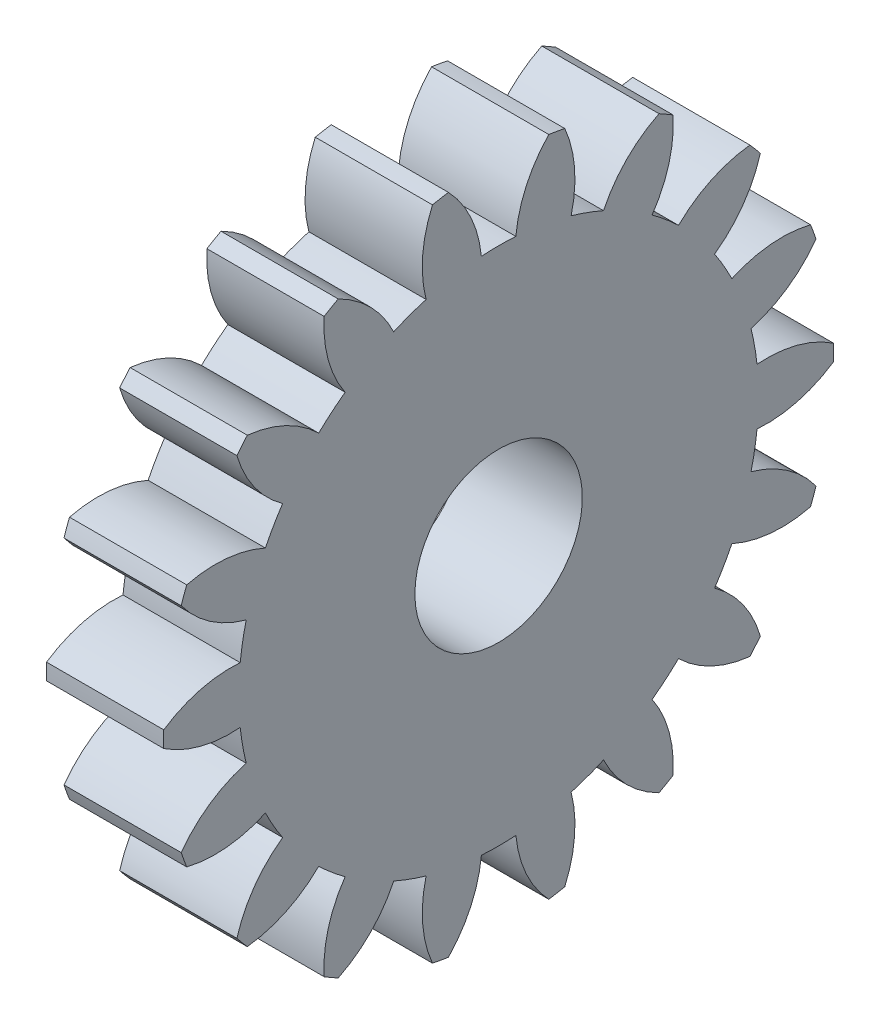
SolidWorks part; units mm, degrees
material "Cedar"
ref_plane "Plane1" through (0, 0, 0) normal (0, 0, 1) x (1, 0, 0)
ref_plane "Plane2" through (0, 0, 0) normal (0, 1, 0) x (1, 0, 0)
ref_plane "Plane3" through (0, 0, 0) normal (1, 0, 0) x (0, 0, -1)
sketch "HoldingSke" plane through (0, 0, 0) normal (0, 1, 0) x (1, 0, 0)
  line L0 (0, 0) -> (483.1367, -156.9806)
  line L1 (-15, 0) -> (100, 0) construction
  line L2 (0, 0) -> (-2.1039, 2.3779)
  line L3 (0, 0) -> (-11.863, 4.5341)
  line L4 (0, 0) -> (8.2133, 2.6687)
  line L5 (0, 0) -> (-47.5972, -17.7524)
  line L6 (0, 0) -> (-3.6847, -2.4861)
  line L7 (-2.1039, 2.3779) -> (8.8308, 51.9871)
  line L8 (-76.2, 54.61) -> (-69.596, 54.61)
  line L9 (-71.009, 38.7566) -> (-53.1078, 45.2721)
  line L10 (-76.2, 71.12) -> (104.1128, 71.12)
  line L11 (0, 0) -> (-4.445, 0)
  line L12 (-76.2, 101.6) -> (-76.1492, 101.6)
  line L13 (24.9733, 27.94) -> (52.9518, 28.4284)
  line L14 (24.9733, 27.94) -> (25.0241, 27.9398)
  line L15 (24.9733, 27.94) -> (100.4021, 29.52)
  circle A0 centre (0, 0) radius 3.175
  circle A1 centre (0, 0) radius 9.8552
  circle A2 centre (0, 0) radius 38.1
  circle A3 centre (0, 0) radius 3.175
  dimension "MHD" = 19.7104
  dimension "Hub_dia" = 76.2
  dimension "Bore" = 6.35
  dimension "MBD" = 6.35
  dimension "Num_teeth" = 18
  dimension "Pitch_radius" = 180.3128
  dimension "Pitch" = 508
  dimension "Width" = 4.445
  dimension "Overall_len" = 50.8
  dimension "Show_teeth" = 18
  dimension "Thickness" = 4.445
  dimension "OAL" = 50.8001
  dimension "T_dim" = 6.604
  dimension "Ap" = 20
  dimension "H" = 19.05
  dimension "Backlash" = 0.0508
  dimension "Addendum_fac" = 1
  dimension "Dedendum_fac" = 1.2
  dimension "Clearance_fac" = 0.2
  dimension "Dedendum_add" = 0.0508
sketch "BasProSke" plane through (0, 0, 0) normal (0, 1, 0) x (1, 0, 0)
  line L0 (-10, 0) -> (60, 0) construction
  line L1 (0, 0) -> (0, 12.7)
  line L2 (0, 0) -> (4.445, 0)
  line L3 (4.445, 0) -> (4.445, 12.7)
  line L4 (4.445, 12.7) -> (0, 12.7)
  dimension "Diameter" = 25.4
  dimension "Thickness" = 4.445
revolve "Base-Revolve" add sketch "BasProSke" angle 360 about L0
sketch "TooCutSke" plane through (0, 0, 0) normal (1, 0, 0) x (0, 0, -1)
  line L1 (0, 0) -> (0, 107) construction
  line L2 (0, 0) -> (-1.085, 11.3784) construction
  line L3 (0, 0) -> (-3.9571, 22.4417) construction
  line L4 (-1.085, 11.3784) -> (-1.9785, 11.2208) construction
  arc A0 (0.6537, 9.8335) -> (-0.6537, 9.8335) centre (0, 0) ccw
  arc A1 (1.9234, 12.5792) -> (-1.9234, 12.5792) centre (0, 0) ccw
  circle A2 centre (0, 0) radius 11.43 construction
  circle A3 centre (0, 0) radius 10.7407 construction
  arc A4 (-0.6537, 9.8335) -> (-1.9234, 12.5792) centre (-5.2046, 9.3954) ccw
  arc A5 (1.9234, 12.5792) -> (0.6537, 9.8335) centre (5.2046, 9.3954) ccw
  dimension "Root_dia" = 19.7104
  dimension "Overcut_dia" = 25.4508
  dimension "Pitch_dia" = 22.86
  dimension "Base_dia" = 21.4814
  dimension "Flank_rad" = 4.572
  dimension "Half_ang" = 10
  dimension "Half_CT" = 0.9073
extrude "ToothCut" cut sketch "TooCutSke" along normal through all
fillet "Breaks" [suppressed] radius 0.0254
fillet "RootFillets" [suppressed] radius 0.3048
pattern_circular "TeethCuts" count 18 every 20 about axis through (-10, 0, 0) along (1, 0, 0) of "ToothCut", "RootFillets", "Breaks"
sketch "HubNeaOneSke" plane through (0, 0, 0) normal (-1, 0, 0) x (0, 0, 1)
  circle A0 centre (0, 0) radius 9.8552
  dimension "Diameter" = 19.7104
extrude "HubNearOne" [suppressed] add sketch "HubNeaOneSke" along normal blind 46.3551
sketch "HubNeaBotSke" plane through (0, 0, 0) normal (-1, 0, 0) x (0, 0, 1)
  circle A0 centre (0, 0) radius 9.8552
  dimension "Diameter" = 19.7104
extrude "HubNearBoth" [suppressed] add sketch "HubNeaBotSke" along normal blind 23.1775
ref_plane "FarPln" through (4.445, 0, 0) normal (1, 0, 0) x (0, 0, -1)
sketch "HubFarSke" plane through (4.445, 0, 0) normal (1, 0, 0) x (0, 0, -1)
  circle A0 centre (0, 0) radius 9.8552
  dimension "Diameter" = 19.7104
extrude "HubFar" [suppressed] add sketch "HubFarSke" along normal blind 23.1775
sketch "BorSke" plane through (0, 0, 0) normal (1, 0, 0) x (0, 0, -1)
  circle A0 centre (0, 0) radius 3.175
  dimension "Diameter" = 6.35
extrude "Bore" cut sketch "BorSke" along normal mid plane 101.6001
sketch "KeySke" plane through (0, 0, 0) normal (1, 0, 0) x (0, 0, -1)
  line L0 (-0.127, 0) -> (-0.127, 3.429)
  line L1 (-0.127, 3.429) -> (0.127, 3.429)
  line L2 (0.127, 3.429) -> (0.127, 0)
  line L3 (0, 0) -> (0, 34) construction
  line L4 (-0.127, 0) -> (0.127, 0)
  dimension "Offset" = 3.429
  dimension "Width" = 0.254
extrude "Keyway" [suppressed] cut sketch "KeySke" along normal mid plane 101.6001
pattern_circular "Keyway2" [suppressed] count 2 every 90 about axis through (-10, 0, 0) along (1, 0, 0)
sketch "Sketch2" plane through (0, 0, 0) normal (-1, 0, 0) x (0, 0, 1)
  circle A0 centre (0, 0) radius 11.43
  dimension "D1" = 22.86
equation "' \"Pitch@HoldingSke\" = 4"
equation "' \"Num_teeth@HoldingSke\" = 12"
equation "' \"Ap@HoldingSke\" =  20"
equation "' \"Width@HoldingSke\" = 0.5"
equation "' \"Hub_dia@HoldingSke\"= 1"
equation "' \"Overall_len@HoldingSke\" = 1.0"
equation "' \"Bore@HoldingSke\" = 0.75"
equation "' \"T_dim@HoldingSke\" = 0.85"
equation "' \"Width@KeySke\" = 0.25"
equation "' \"Show_teeth@HoldingSke\" = 13"
equation "' \"Backlash@HoldingSke\" = 0.009"
equation "' \"Addendum_fac@HoldingSke\" = 1.0"
equation "' \"Dedendum_fac@HoldingSke\" = 1.25"
equation "' \"Dedendum_add@HoldingSke\" = 0.00005"
equation "' \"Clearance_fac@HoldingSke\" = 0.25"
equation "' \"Pitch@HoldingSke\" = 0.5"
equation "' \"Num_teeth@HoldingSke\" = 23"
equation "' \"Show_teeth@HoldingSke\" = 23"
equation "' \"Backlash@HoldingSke\" = 0.0375"
equation "\"Overcut_dia@TooCutSke\" = (\"Num_teeth@HoldingSke\" + 2 * \"Addendum_fac@HoldingSke\") / \"Pitch@HoldingSke\" + 0.002"
equation "\"Pitch_dia@TooCutSke\" = \"Num_teeth@HoldingSke\" / \"Pitch@HoldingSke\""
equation "\"Base_dia@TooCutSke\" = \"Num_teeth@HoldingSke\" / \"Pitch@HoldingSke\" * cos((\"Ap@HoldingSke\"  * 3.14159265 / 180))"
equation "\"Root_dia@TooCutSke\" = (\"Num_teeth@HoldingSke\" + 2) / \"Pitch@HoldingSke\" - 2 * (\"Addendum_fac@HoldingSke\" + \"Dedendum_fac@HoldingSke\") / \"Pitch@HoldingSke\" - \"Dedendum_add@HoldingSke\" * 2"
equation "\"Half_ang@TooCutSke\" = 180 / \"Num_teeth@HoldingSke\""
equation "\"Half_CT@TooCutSke\" = \"Num_teeth@HoldingSke\" / \"Pitch@HoldingSke\" * sin((3.14159265 / 2 / \"Num_teeth@HoldingSke\")) / 2 - 7 * \"Backlash@HoldingSke\" / 4"
equation "\"Flank_rad@TooCutSke\" = \"Num_teeth@HoldingSke\" / \"Pitch@HoldingSke\" / 5"
equation "\"Radius@RootFillets\" = \"Clearance_fac@HoldingSke\" / \"Pitch@HoldingSke\" + \"Dedendum_add@HoldingSke\""
equation "\"Break_rad@Breaks\" = 0.02 / \"Pitch@HoldingSke\""
equation "\"Thickness@HoldingSke\" = \"Width@HoldingSke\""
equation "\"OAL@HoldingSke\" = \"Thickness@HoldingSke\""
equation "\"MHD@HoldingSke\" = (\"Num_teeth@HoldingSke\" + 2) / \"Pitch@HoldingSke\" - 2 * (\"Addendum_fac@HoldingSke\" + \"Dedendum_fac@HoldingSke\")  / \"Pitch@HoldingSke\" - \"Dedendum_add@HoldingSke\" * 2"
equation "\"MBD@HoldingSke\" = (\"Num_teeth@HoldingSke\" + 2) / \"Pitch@HoldingSke\" - 2 * (\"Addendum_fac@HoldingSke\" + \"Dedendum_fac@HoldingSke\")  / \"Pitch@HoldingSke\" - \"Dedendum_add@HoldingSke\" * 2 - 0.002"
equation "\"MHD@HoldingSke\" = ((sgn( \"MHD@HoldingSke\" - \"Hub_dia@HoldingSke\" )-1)*( \"MHD@HoldingSke\" - \"Hub_dia@HoldingSke\" ))/-2+ \"Hub_dia@HoldingSke\""
equation "\"MBD@HoldingSke\" = ((sgn( \"MBD@HoldingSke\" - \"Bore@HoldingSke\" )-1)*( \"MBD@HoldingSke\" - \"Bore@HoldingSke\" ))/-2+ \"Bore@HoldingSke\""
equation "\"OAL@HoldingSke\" = ((sgn( \"OAL@HoldingSke\" - \"Overall_len@HoldingSke\" )+1)*( \"OAL@HoldingSke\" - \"Overall_len@HoldingSke\" ))/2 + \"Overall_len@HoldingSke\" + 0.000002"
equation "\"Num_teeth@TeethCuts\" = int( \"Show_teeth@HoldingSke\" ) + 1"
equation "\"Num_teeth@TeethCuts\" = ((sgn( \"Num_teeth@TeethCuts\" - \"Num_teeth@HoldingSke\" )-1)*( \"Num_teeth@TeethCuts\" - \"Num_teeth@HoldingSke\" ))/-2+ \"Num_teeth@HoldingSke\""
equation "\"Num_teeth@TeethCuts\" = ((sgn( \"Num_teeth@TeethCuts\" - 2.0)+1)*( \"Num_teeth@TeethCuts\" - 2.0))/2 +2.0"
equation "\"Angle@TeethCuts\" = 360.0 / \"Num_teeth@HoldingSke\""
equation "\"Diameter@BasProSke\" = (\"Num_teeth@HoldingSke\" + 2 * \"Addendum_fac@HoldingSke\") / \"Pitch@HoldingSke\""
equation "\"Thickness@BasProSke\"  = \"Thickness@HoldingSke\""
equation "' \"Fillet_rad@BasProSke\" =  \"Thickness@HoldingSke\" * 0.05"
equation "\"MHD@HoldingSke\" = ((sgn( \"MHD@HoldingSke\" - \"Root_dia@TooCutSke\" )-1)*( \"MHD@HoldingSke\" - \"Root_dia@TooCutSke\" ))/-2+ \"Root_dia@TooCutSke\""
equation "\"Diameter@HubNeaOneSke\" = \"MHD@HoldingSke\""
equation "\"Length@HubNearOne\" = \"OAL@HoldingSke\" - \"Thickness@BasProSke\""
equation "\"Diameter@HubNeaBotSke\" = \"MHD@HoldingSke\""
equation "\"Length@HubNearBoth\" = ( \"OAL@HoldingSke\" - \"Thickness@BasProSke\" ) / 2.0"
equation "\"Thickness@FarPln\" = \"Thickness@BasProSke\""
equation "\"Diameter@HubFarSke\" = \"MHD@HoldingSke\""
equation "\"Length@HubFar\" = ( \"OAL@HoldingSke\" - \"Thickness@BasProSke\" ) / 2.0"
equation "\"Diameter@BorSke\" = \"MBD@HoldingSke\""
equation "\"D1@Bore\" = \"OAL@HoldingSke\" * 2.0"
equation "\"D1@Keyway\" = \"OAL@HoldingSke\" * 2.0"
equation "\"Offset@KeySke\" = \"T_dim@HoldingSke\" - \"MBD@HoldingSke\" / 2.0"
